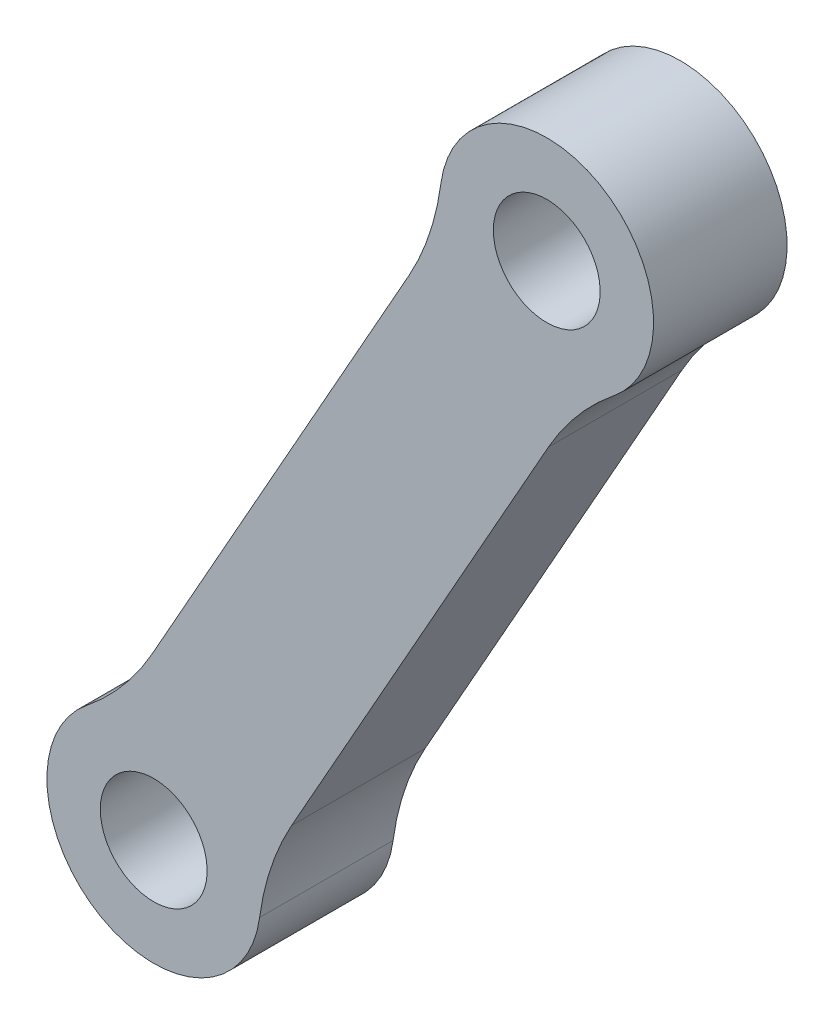
SolidWorks part; units mm, degrees
ref_plane "Front Plane" through (0, 0, 0) normal (0, 0, 1) x (1, 0, 0)
ref_plane "Top Plane" through (0, 0, 0) normal (0, 1, 0) x (1, 0, 0)
ref_plane "Right Plane" through (0, 0, 0) normal (1, 0, 0) x (0, 0, -1)
ref_plane "Plane1" through (0, 0, 63) normal (0, 0, 1) x (1, 0, 0)
sketch "Sketch1" plane through (0, 0, 63) normal (0, 0, 1) x (1, 0, 0)
  line L0 (13.4101, 15.1998) -> (23.0304, 32.2852)
  line L1 (17.8022, 35.229) -> (8.1819, 18.1436)
  arc A0 (23.0304, 32.2852) -> (25.4738, 35.1689) centre (31.744, 27.3789) cw
  arc A1 (25.4738, 35.1689) -> (19.0008, 38.8136) centre (22.9657, 38.2849) ccw
  arc A2 (19.0008, 38.8136) -> (17.8022, 35.229) centre (9.0885, 40.1354) cw
  arc A3 (8.1819, 18.1436) -> (5.7385, 15.2599) centre (-0.5317, 23.0499) cw
  arc A4 (5.7385, 15.2599) -> (12.2115, 11.6152) centre (8.2466, 12.1439) ccw
  arc A5 (12.2115, 11.6152) -> (13.4101, 15.1998) centre (22.1238, 10.2934) cw
  circle A6 centre (8.2466, 12.1439) radius 2
  circle A7 centre (22.9657, 38.2849) radius 2
extrude "Boss-Extrude1" add sketch "Sketch1" against normal blind 5
